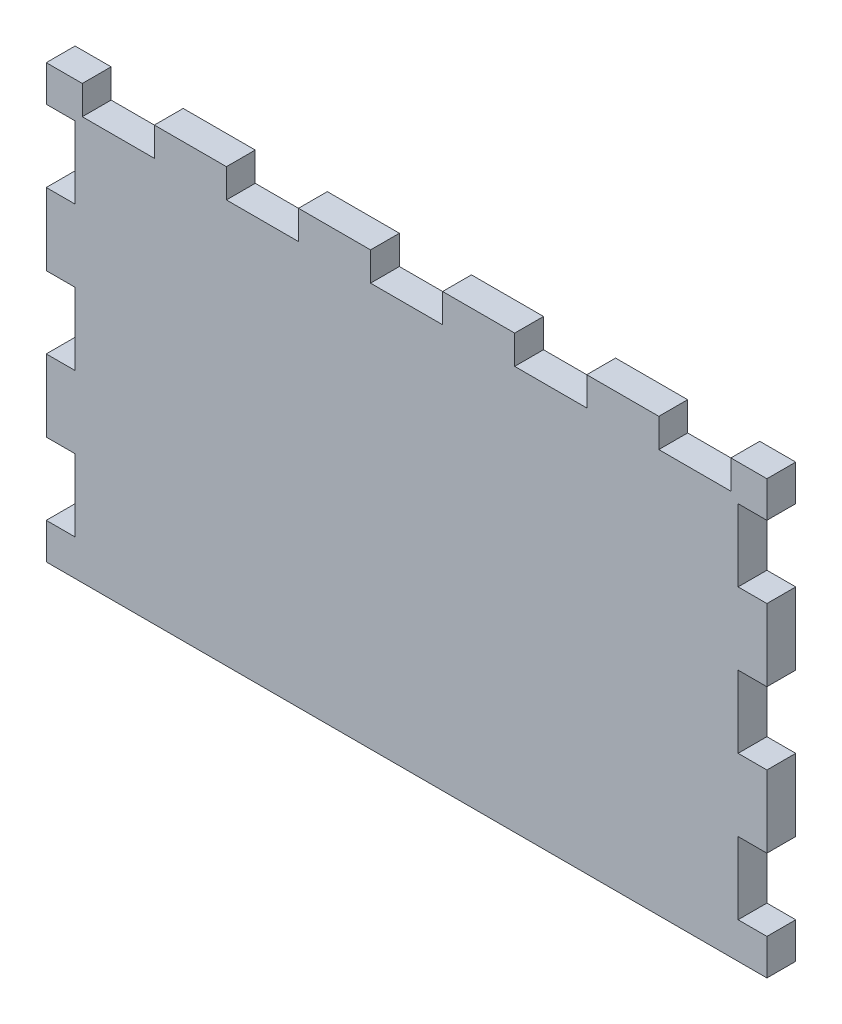
SolidWorks part; units mm, degrees
ref_plane "Front Plane" through (0, 0, 0) normal (0, 0, 1) x (1, 0, 0)
ref_plane "Top Plane" through (0, 0, 0) normal (0, 1, 0) x (1, 0, 0)
ref_plane "Right Plane" through (0, 0, 0) normal (1, 0, 0) x (0, 0, -1)
sketch "Sketch1" plane through (0, 0, 0) normal (0, 0, 1) x (1, 0, 0)
  line L0 (-50, 30) -> (-30, 30)
  line L1 (-50, -30) -> (50, -30)
  line L2 (-50, -30) -> (-50, 30)
  line L3 (-50, 30) -> (50, 30)
  line L4 (50, -30) -> (50, 30)
  line L5 (0, 30) -> (0, -30) construction
  line L6 (-50, 0) -> (50, 0) construction
  line L7 (-30, 30) -> (-10, 30)
  line L8 (-10, 30) -> (10, 30)
  line L9 (10, 30) -> (30, 30)
  line L10 (50, -30) -> (50, -10)
  line L11 (50, -10) -> (50, 10)
  line L12 (-50, -30) -> (-50, -10)
  line L13 (-45, 26) -> (-35, 26)
  line L14 (-45, 26) -> (-45, 34)
  line L15 (-45, 34) -> (-35, 34)
  line L16 (-35, 26) -> (-35, 34)
  line L17 (-40, 34) -> (-40, 26) construction
  line L18 (-45, 30) -> (-35, 30) construction
  line L19 (-25, 26) -> (-15, 26)
  line L20 (-25, 26) -> (-25, 34)
  line L21 (-25, 34) -> (-15, 34)
  line L22 (-15, 26) -> (-15, 34)
  line L23 (-20, 34) -> (-20, 26) construction
  line L24 (-25, 30) -> (-15, 30) construction
  line L25 (-5, 26) -> (5, 26)
  line L26 (-5, 26) -> (-5, 34)
  line L27 (-5, 34) -> (5, 34)
  line L28 (5, 26) -> (5, 34)
  line L29 (0, 34) -> (0, 26) construction
  line L30 (-5, 30) -> (5, 30) construction
  line L31 (15, 26) -> (25, 26)
  line L32 (15, 26) -> (15, 34)
  line L33 (15, 34) -> (25, 34)
  line L34 (25, 26) -> (25, 34)
  line L35 (20, 34) -> (20, 26) construction
  line L36 (15, 30) -> (25, 30) construction
  line L37 (35, 26) -> (45, 26)
  line L38 (35, 26) -> (35, 34)
  line L39 (35, 34) -> (45, 34)
  line L40 (45, 26) -> (45, 34)
  line L41 (40, 34) -> (40, 26) construction
  line L42 (35, 30) -> (45, 30) construction
  line L43 (46, 25) -> (54, 25)
  line L44 (46, 25) -> (46, 15)
  line L45 (46, 15) -> (54, 15)
  line L46 (54, 25) -> (54, 15)
  line L47 (50, 15) -> (50, 25) construction
  line L48 (46, 20) -> (54, 20) construction
  line L49 (46, 5) -> (54, 5)
  line L50 (46, 5) -> (46, -5)
  line L51 (46, -5) -> (54, -5)
  line L52 (54, 5) -> (54, -5)
  line L53 (50, -5) -> (50, 5) construction
  line L54 (46, 0) -> (54, 0) construction
  line L55 (46, -15) -> (54, -15)
  line L56 (46, -15) -> (46, -25)
  line L57 (46, -25) -> (54, -25)
  line L58 (54, -15) -> (54, -25)
  line L59 (50, -25) -> (50, -15) construction
  line L60 (46, -20) -> (54, -20) construction
  line L61 (-50, -10) -> (-50, 10)
  line L63 (-54, 25) -> (-46, 25)
  line L64 (-54, 25) -> (-54, 15)
  line L65 (-54, 15) -> (-46, 15)
  line L66 (-46, 25) -> (-46, 15)
  line L67 (-50, 15) -> (-50, 25) construction
  line L68 (-54, 20) -> (-46, 20) construction
  line L69 (-54, 5) -> (-46, 5)
  line L70 (-54, 5) -> (-54, -5)
  line L71 (-54, -5) -> (-46, -5)
  line L72 (-46, 5) -> (-46, -5)
  line L73 (-50, -5) -> (-50, 5) construction
  line L74 (-54, 0) -> (-46, 0) construction
  line L75 (-54, -15) -> (-46, -15)
  line L76 (-54, -15) -> (-54, -25)
  line L77 (-54, -25) -> (-46, -25)
  line L78 (-46, -15) -> (-46, -25)
  line L79 (-50, -25) -> (-50, -15) construction
  line L80 (-54, -20) -> (-46, -20) construction
  line L81 (-50, -25) -> (-54, -25)
  line L82 (-50, -25) -> (-50, -30)
  line L83 (-50, -30) -> (-54, -30)
  line L84 (-54, -25) -> (-54, -30)
  line L85 (-50, -15) -> (-54, -15)
  line L86 (-50, -15) -> (-50, -5)
  line L87 (-50, -5) -> (-54, -5)
  line L88 (-54, -15) -> (-54, -5)
  line L89 (-50, 5) -> (-54, 5)
  line L90 (-50, 5) -> (-50, 15)
  line L91 (-50, 15) -> (-54, 15)
  line L92 (-54, 5) -> (-54, 15)
  line L93 (-50, 25) -> (-54, 25)
  line L94 (-50, 25) -> (-50, 30)
  line L95 (-50, 30) -> (-54, 30)
  line L96 (-54, 25) -> (-54, 30)
  line L97 (-54, 30) -> (-45, 30)
  line L98 (-54, 30) -> (-54, 34)
  line L99 (-54, 34) -> (-45, 34)
  line L100 (-45, 30) -> (-45, 34)
  line L101 (-35, 34) -> (-25, 34)
  line L102 (-35, 34) -> (-35, 30)
  line L103 (-35, 30) -> (-25, 30)
  line L104 (-25, 34) -> (-25, 30)
  line L105 (-15, 34) -> (-5, 34)
  line L106 (-15, 34) -> (-15, 30)
  line L107 (-15, 30) -> (-5, 30)
  line L108 (-5, 34) -> (-5, 30)
  line L109 (5, 34) -> (15, 34)
  line L110 (5, 34) -> (5, 30)
  line L111 (5, 30) -> (15, 30)
  line L112 (15, 34) -> (15, 30)
  line L113 (25, 34) -> (35, 34)
  line L114 (25, 34) -> (25, 30)
  line L115 (25, 30) -> (35, 30)
  line L116 (35, 34) -> (35, 30)
  line L117 (45, 34) -> (54, 34)
  line L118 (45, 34) -> (45, 30)
  line L119 (45, 30) -> (54, 30)
  line L120 (54, 34) -> (54, 30)
  line L121 (54, 30) -> (50, 30)
  line L122 (54, 30) -> (54, 25)
  line L123 (54, 25) -> (50, 25)
  line L124 (50, 30) -> (50, 25)
  line L125 (50, 15) -> (54, 15)
  line L126 (50, 15) -> (50, 5)
  line L127 (50, 5) -> (54, 5)
  line L128 (54, 15) -> (54, 5)
  line L129 (50, 20) -> (54, 20)
  line L130 (50, 20) -> (50, 10)
  line L131 (50, 10) -> (54, 10)
  line L132 (54, 20) -> (54, 10)
  line L133 (50, -5) -> (54, -5)
  line L134 (50, -5) -> (50, -15)
  line L135 (50, -15) -> (54, -15)
  line L136 (54, -5) -> (54, -15)
  line L137 (50, -25) -> (54, -25)
  line L138 (50, -25) -> (50, -30)
  line L139 (50, -30) -> (54, -30)
  line L140 (54, -25) -> (54, -30)
  point P0 (0, 0)
  point P4 (-40, 30)
  point P11 (-20, 30)
  point P12 (20, 30)
  point P13 (0, 30)
  point P14 (40, 30)
  point P15 (50, 20)
  point P16 (50, -20)
  point P17 (50, 0)
  point P18 (-40, 30)
  point P22 (-20, 30)
  point P29 (20, 30)
  point P33 (40, 30)
  point P37 (50, 20)
  point P44 (50, -20)
  point P48 (-50, -20)
  point P51 (-50, 0)
  point P52 (-50, 20)
  point P53 (-50, 20)
  point P65 (-50, -20)
  dimension "D1" = 60
  dimension "D2" = 100
  dimension "D3" = 20
  dimension "D4" = 20
  dimension "D5" = 20
  dimension "D6" = 20
  dimension "D7" = 20
  dimension "D8" = 20
  dimension "D9" = 20
  dimension "D10" = 20
  dimension "D11" = 10
  dimension "D12" = 10
  dimension "D13" = 10
  dimension "D14" = 10
  dimension "D15" = 10
  dimension "D16" = 10
  dimension "D17" = 10
  dimension "D18" = 10
  dimension "D19" = 20
  dimension "D20" = 10
  dimension "D21" = 20
  dimension "D22" = 10
  dimension "D23" = 20
  dimension "D24" = 10
  dimension "D25" = 8
  dimension "D26" = 8
  dimension "D27" = 8
  dimension "D28" = 8
  dimension "D29" = 8
  dimension "D30" = 8
  dimension "D31" = 8
  dimension "D32" = 8
  dimension "D33" = 8
  dimension "D34" = 8
  dimension "D35" = 8
  dimension "D36" = 10
  dimension "D37" = 10
  dimension "D38" = 10
  dimension "D39" = 10
  dimension "D40" = 10
  dimension "D41" = 10
  dimension "D42" = 10
  dimension "D43" = 10
  dimension "D44" = 10
  dimension "D45" = 10
  dimension "D46" = 10
extrude "Boss-Extrude1" add sketch "Sketch1" along normal blind 4 contours L75 L78 L77 L2 L1 L4 L57 L56 L55 L10 L51 L50 L49 L11 L45 L44 L43 L3 L40 L37 L38 L34 L31 L32 L28 L25 L26 L22 L19 L20 L0 L16 L13 L14 L63 L66 L65 L61
